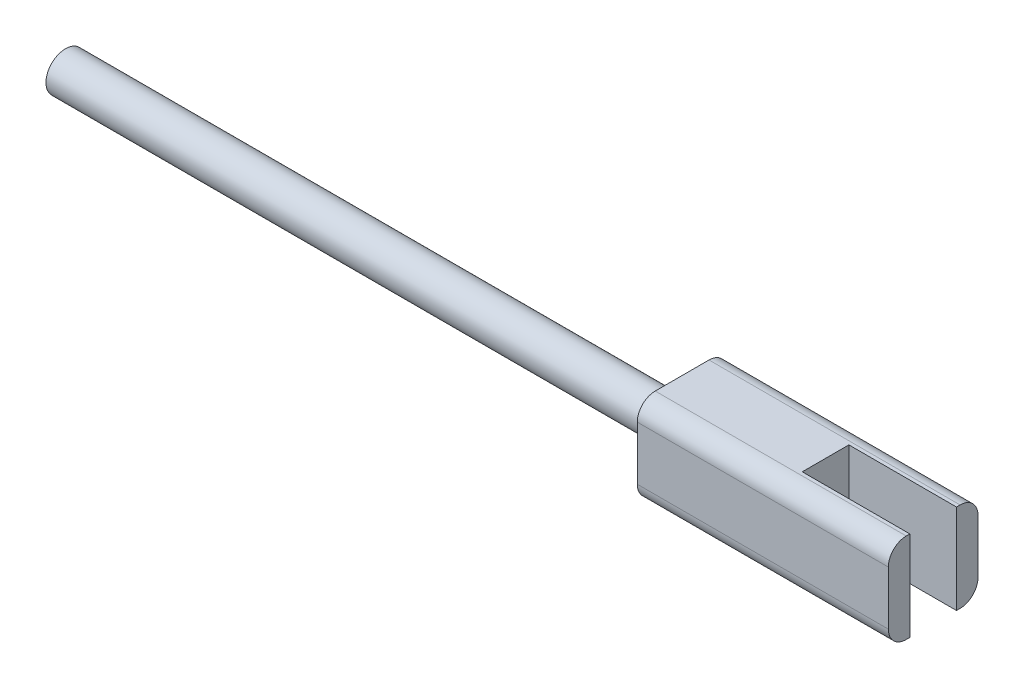
SolidWorks part; units mm, degrees
ref_plane "Front Plane" through (0, 0, 0) normal (0, 0, 1) x (1, 0, 0)
ref_plane "Top Plane" through (0, 0, 0) normal (0, 1, 0) x (1, 0, 0)
ref_plane "Right Plane" through (0, 0, 0) normal (1, 0, 0) x (0, 0, -1)
sketch "Sketch1" plane through (0, 0, 0) normal (1, 0, 0) x (0, 0, -1)
  circle A0 centre (0, 0) radius 1.09
extrude "Boss-Extrude1" add sketch "Sketch1" along normal blind 36.385
ref_plane "Plane1" through (34.385, 0, 0) normal (1, 0, 0) x (0, 0, -1)
sketch "Sketch2" plane through (34.385, 0, 0) normal (1, 0, 0) x (0, 0, -1)
  line L0 (-1.5, -2.5) -> (1.5, -2.5)
  line L1 (2.5, -1.5) -> (2.5, 1.5)
  line L2 (1.5, 2.5) -> (-1.5, 2.5)
  line L3 (-2.5, 1.5) -> (-2.5, -1.5)
  arc A0 (1.5, -2.5) -> (2.5, -1.5) centre (1.5, -1.5) ccw
  arc A1 (2.5, 1.5) -> (1.5, 2.5) centre (1.5, 1.5) ccw
  arc A2 (-1.5, 2.5) -> (-2.5, 1.5) centre (-1.5, 1.5) ccw
  arc A3 (-2.5, -1.5) -> (-1.5, -2.5) centre (-1.5, -1.5) ccw
extrude "Boss-Extrude2" add sketch "Sketch2" along normal blind 14
sketch "Sketch3" plane through (0, 0, 0) normal (0, 1, 0) x (1, 0, 0)
  line L0 (42.385, 1.3) -> (49.385, 1.3)
  line L1 (49.385, 1.3) -> (49.385, -1.3)
  line L2 (49.385, -1.3) -> (42.385, -1.3)
  line L3 (42.385, -1.3) -> (42.385, 1.3)
extrude "Cut-Extrude1" cut sketch "Sketch3" against normal through all and the other way through all
